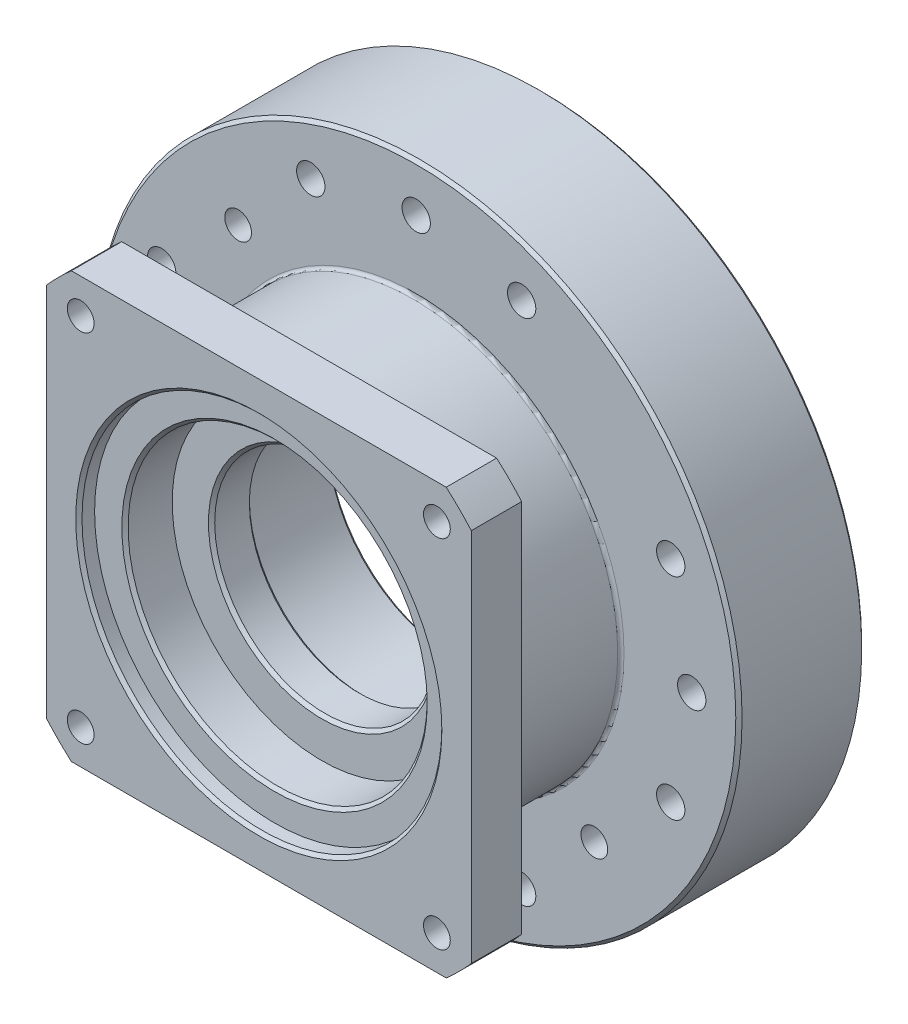
SolidWorks part; units mm, degrees
material "Q235"
ref_plane "前视基准面" through (0, 0, 0) normal (0, 0, 1) x (1, 0, 0)
ref_plane "上视基准面" through (0, 0, 0) normal (0, 1, 0) x (1, 0, 0)
ref_plane "右视基准面" through (0, 0, 0) normal (1, 0, 0) x (0, 0, -1)
sketch "草图1" plane through (0, 0, 0) normal (0, 0, 1) x (1, 0, 0)
  circle A1 centre (0, 0) radius 102.5
  dimension "D2" = 205
extrude "凸台-拉伸1" add sketch "草图1" along normal blind 40
sketch "草图3" plane through (0, 0, 0) normal (0, 0, -1) x (-1, 0, 0)
  circle A0 centre (0, 0) radius 95.25
  dimension "D1" = 190.5
extrude "切除-拉伸1" cut sketch "草图3" against normal blind 4
sketch "草图5" plane through (0, 0, 4) normal (0, 0, -1) x (-1, 0, 0)
  circle A0 centre (0, 0) radius 80
  dimension "D1" = 160
extrude "切除-拉伸3" cut sketch "草图5" against normal blind 15
sketch "草图6" plane through (0, 0, 40) normal (0, 0, 1) x (1, 0, 0)
  line L1 (65, -65) -> (-65, -65)
  line L2 (65, -65) -> (65, 65)
  line L3 (65, 65) -> (-65, 65)
  line L4 (-65, -65) -> (-65, 65)
  line L5 (65, -65) -> (-65, 65) construction
  line L6 (65, 65) -> (-65, -65) construction
  point P0 (0, 0)
  dimension "D1" = 130
  dimension "D2" = 130
extrude "凸台-拉伸2" add sketch "草图6" along normal blind 34
sketch "草图7" plane through (0, 0, 74) normal (0, 0, 1) x (1, 0, 0)
  circle A0 centre (0, 0) radius 47.5
  dimension "D1" = 95
extrude "切除-拉伸4" cut sketch "草图7" against normal blind 4
chamfer "倒角1" distance 10 angle 45 4 edges at (-65, -65, 57) (65, -65, 57) (65, 65, 57) (-65, 65, 57)
sketch "草图8" plane through (0, 0, 70) normal (0, 0, 1) x (1, 0, 0)
  circle A0 centre (0, 0) radius 35
  dimension "D1" = 70
extrude "切除-拉伸5" cut sketch "草图8" against normal through all
sketch "草图9" plane through (0, 0, 19) normal (0, 0, -1) x (-1, 0, 0)
  circle A0 centre (0, 0) radius 79.5
  dimension "D1" = 159
extrude "切除-拉伸7" cut sketch "草图9" against normal blind 8
hole_wizard "M8 螺纹孔1" [suppressed] positions "草图12" profile "草图13" tap size "M8" standard "GB"
sketch "草图12" plane through (0, 0, 74) normal (0, 0, 1) x (1, 0, 0)
  line L0 (0, 0) -> (-40.6586, -40.6586) construction
  line L2 (0, 0) -> (0, -118.6351) construction
  circle A0 centre (0, 0) radius 57.5 construction
  point P0 (-40.6586, -40.6586)
  dimension "D1" = 45
  dimension "D2" = 115
cosmetic thread "孔螺蚊线4" [suppressed] parameters "D1"=16, "D2"=8
sketch "草图13" plane through (-40.6586, -40.6586, 74) normal (1, 0, 0) x (0, -1, 0)
  line L0 (0, 0) -> (0, 21.7929)
  line L1 (0, 21.7929) -> (3.4, 19.75)
  line L2 (3.4, 19.75) -> (3.4, 0)
  line L5 (3.4, 0) -> (0, 0)
  line L10 (0, 21.7929) -> (-3.4, 19.75) construction
  line L11 (0, -6.35) -> (0, 107.95) construction
  dimension "螺纹孔钻头直径" = 6.8
  dimension "螺纹孔钻头深度" = 19.75
  dimension "导头角度" = 118
sketch "草图14" plane through (0, 0, 0) normal (0, 0, -1) x (-1, 0, 0)
  line L0 (0, 0) -> (87.5, 0) construction
  circle A0 centre (87.5, 0) radius 4.5
  circle A1 centre (0, 0) radius 87.5 construction
  dimension "D1" = 175
  dimension "D2" = 9
extrude "切除-拉伸8" cut sketch "草图14" against normal through all
pattern_circular "阵列(圆周)1" count 16 over 360 about axis through (0, 0, 0) along (0, 0, 1) skipping 2, 6, 10, 14 of "切除-拉伸8"
sketch "草图15" plane through (0, 0, 40) normal (0, 0, 1) x (1, 0, 0)
  line L0 (0, 0) -> (56.5685, -56.5685) construction
  line L1 (0, 0) -> (0, -80) construction
  circle A0 centre (0, 0) radius 80 construction
  dimension "D1" = 160
  dimension "D2" = 45
hole_wizard "M10 螺纹孔1" positions "3D草图2" profile "草图17" tap size "M10" standard "GB"
sketch3d "3D草图2"
  line L0 (0, -87.5, 40) -> (0, 0, 0) construction
  line L1 (0, -87.5, 40) -> (0, -87.5, 4) construction
  line L6 (33.4848, -80.8395, 40) -> (0, 0, 40) construction
  line L7 (33.4848, -80.8395, 40) -> (33.4848, -80.8395, 4) construction
  line L8 (0, 0, 40) -> (0, 0, 0) construction
  line L10 (0, 0, 0) -> (61.8718, -61.8718, 74) construction
  line L13 (0, 0, 0) -> (56.5685, -56.5685, 40) construction
  point P0 (56.5685, -56.5685, 40)
sketch "草图17" plane through (56.5685, -56.5685, 40) normal (1, 0, 0) x (0, -1, 0)
  line L0 (0, 0) -> (0, 40)
  line L1 (0, 40) -> (4.25, 40)
  line L2 (4.25, 40) -> (4.25, 0)
  line L5 (4.25, 0) -> (0, 0)
  line L11 (0, -6.35) -> (0, 107.95) construction
  dimension "通孔螺纹孔钻头直径" = 8.5
  dimension "通孔螺纹孔钻头深度" = 40
cosmetic thread "孔螺蚊线5" parameters "D2"=10
chamfer "倒角2" [suppressed] distance 0.5 angle 45
chamfer "倒角3" distance 0.5 angle 45 1 edges at (-95.25, 0, 0)
chamfer "倒角4" distance 0.5 angle 45 1 edges at (-56.5685, 56.5685, 4)
pattern_circular "阵列(圆周)2" [suppressed] count 4 over 360
sketch "草图21" plane through (0, 0, 74) normal (0, 0, 1) x (1, 0, 0)
  circle A0 centre (0, 0) radius 65
  dimension "D1" = 130
extrude "切除-拉伸11" cut sketch "草图21" against normal up to surface (34 mm away) flip side to cut up to face at (-76.3395, 33.4848, 40)
fillet "圆角1" radius 1 1 edges at (65, 0, 40)
sketch "草图22" plane through (0, 0, 27) normal (0, 0, -1) x (-1, 0, 0)
  circle A0 centre (0, 0) radius 40
  dimension "D1" = 80
extrude "切除-拉伸12" cut sketch "草图22" against normal blind 30
pattern_circular "阵列(圆周)3" count 2 over 360 about axis through (0, 0, 0) along (0, 0, 1) of "M10 螺纹孔1"
sketch "草图24" plane through (0, 0, 0) normal (0, 1, 0) x (1, 0, 0)
  line L0 (0, 0) -> (0, -116.7871) construction
  line L1 (-90, -74) -> (-47.5, -74)
  line L2 (-90, -74) -> (-90, -90)
  line L3 (-90, -90) -> (-57.15, -90)
  line L4 (-57.15, -90) -> (-57.15, -85)
  line L5 (-57.15, -85) -> (-47.5, -85)
  line L6 (-47.5, -74) -> (-47.5, -85)
  line L7 (-47.5, -74) -> (47.5, -74) construction
  line L8 (-65, -74) -> (65, -74) construction
  dimension "D1" = 16
  dimension "D2" = 180
  dimension "D3" = 5
  dimension "D4" = 95
  dimension "D5" = 114.3
revolve "旋转2" add sketch "草图24" angle 360 about L0
sketch "草图26" plane through (0, 0, 90) normal (0, 0, 1) x (1, 0, 0)
  line L1 (-67.5, -67.5) -> (67.5, -67.5)
  line L2 (-67.5, -67.5) -> (-67.5, 67.5)
  line L3 (-67.5, 67.5) -> (67.5, 67.5)
  line L4 (67.5, -67.5) -> (67.5, 67.5)
  line L5 (-67.5, -67.5) -> (67.5, 67.5) construction
  line L6 (-67.5, 67.5) -> (67.5, -67.5) construction
  point P0 (0, 0)
  dimension "D1" = 135
extrude "切除-拉伸13" cut sketch "草图26" against normal up to surface (16 mm away) flip side to cut up to face at (65, 0, 74)
hole_wizard "M10 螺纹孔2" positions "草图28" profile "草图27" tap size "M10" standard "GB"
sketch "草图28" plane through (0, 0, 90) normal (0, 0, 1) x (1, 0, 0)
  line L0 (0, 0) -> (56.5685, 56.5685) construction
  line L2 (0, 0) -> (0, 102.5) construction
  circle A0 centre (0, 0) radius 80 construction
  circle A1 centre (0, 0) radius 102.5 construction
  point P0 (56.5685, 56.5685)
  dimension "D1" = 160
  dimension "D2" = 45
cosmetic thread "孔螺蚊线6" parameters "D2"=10
sketch "草图27" plane through (56.5685, 56.5685, 90) normal (1, 0, 0) x (0, -1, 0)
  line L0 (0, 0) -> (0, 71)
  line L1 (0, 71) -> (4.25, 71)
  line L2 (4.25, 71) -> (4.25, 0)
  line L5 (4.25, 0) -> (0, 0)
  line L11 (0, -6.35) -> (0, 107.95) construction
  dimension "通孔螺纹孔钻头直径" = 8.5
  dimension "通孔螺纹孔钻头深度" = 71
pattern_circular "阵列(圆周)4" count 4 over 360 about axis through (0, 0, 0) along (0, 0, 1) of "M10 螺纹孔2"
chamfer "倒角6" distance 1 angle 45 5 edges at (-57.15, 0, 90) (-35, 0, 57) (-47.5, 0, 85) (-40, 0, 27) (35, 0, 70)
chamfer "倒角7" distance 1 angle 45 2 edges at (102.5, 0, 0) (102.5, 0, 40)
sketch "草图29" plane through (0, 0, 4) normal (0, 0, -1) x (-1, 0, 0)
  circle A0 centre (-56.5685, -56.5685) radius 5.5
  circle A1 centre (56.5685, 56.5685) radius 6
  dimension "D1" = 11
  dimension "D2" = 12
extrude "切除-拉伸14" cut sketch "草图29" against normal up to surface (23 mm away) up to face at (-41, 0, 27)
